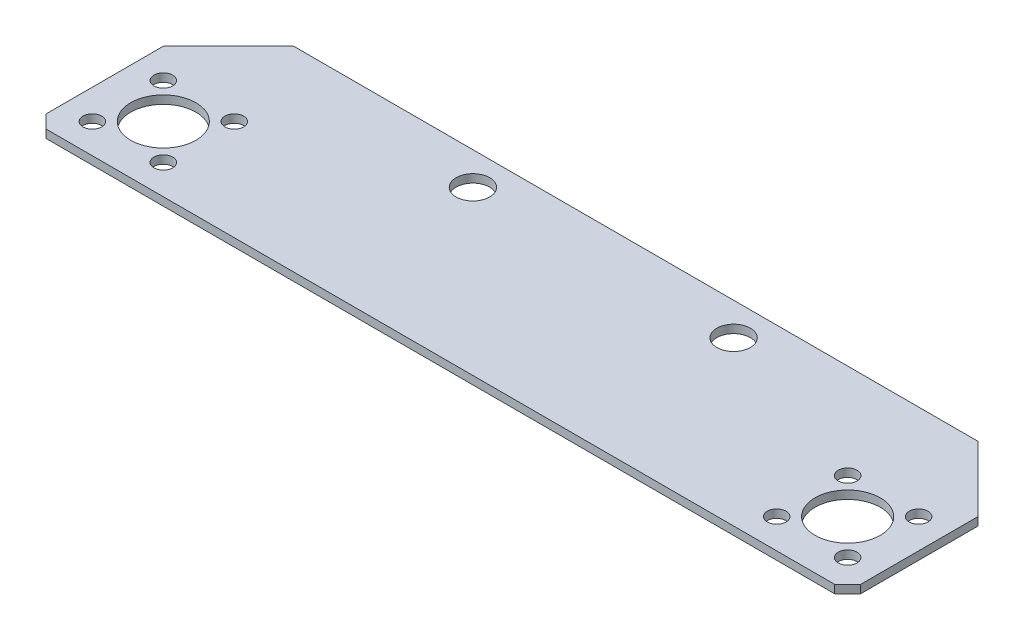
SolidWorks part; units mm, degrees
material "6061 Alloy"
ref_plane "Front Plane" through (0, 0, 0) normal (0, 0, 1) x (1, 0, 0)
ref_plane "Top Plane" through (0, 0, 0) normal (0, 1, 0) x (1, 0, 0)
ref_plane "Right Plane" through (0, 0, 0) normal (1, 0, 0) x (0, 0, -1)
sketch "Sketch1" plane through (0, 0, 0) normal (0, 1, 0) x (1, 0, 0)
  line L1 (0, 0) -> (158.75, 0)
  line L2 (0, 0) -> (0, 38.1)
  line L3 (0, 38.1) -> (158.75, 38.1)
  line L4 (158.75, 0) -> (158.75, 38.1)
  dimension "D1" = 38.1
  dimension "D2" = 158.75
extrude "Boss-Extrude1" add sketch "Sketch1" along normal blind 1.6002
hole_wizard "#27 (0.144) Diameter Hole1" positions "Sketch3" profile "Sketch2" hole size "#27" standard "ANSI Inch" end condition through all
sketch "Sketch3" plane through (0, 1.6002, 0) normal (0, 1, 0) x (1, 0, 0)
  line L0 (79.375, 0) -> (79.375, 38.1) construction
  line L1 (0, 0) -> (158.75, 0) construction
  line L2 (158.75, 38.1) -> (0, 38.1) construction
  line L3 (5.7852, 19.6148) -> (19.6148, 5.7852) construction
  line L6 (19.6148, 19.6148) -> (5.7852, 5.7852) construction
  line L11 (12.7, 12.7) -> (0, 12.7) construction
  line L14 (0, 38.1) -> (0, 0) construction
  point P9 (5.7852, 19.6148)
  point P11 (19.6148, 5.7852)
  point P13 (5.7852, 5.7852)
  point P15 (19.6148, 19.6148)
  point P43 (152.9648, 5.7852)
  point P44 (139.1352, 5.7852)
  point P45 (139.1352, 19.6148)
  point P46 (152.9648, 19.6148)
  dimension "D1" = 19.558
  dimension "D2" = 12.7
  dimension "D3" = 12.7
sketch "Sketch2" plane through (5.7852, 1.6002, -19.6148) normal (1, 0, 0) x (0, 0, 1)
  line L0 (0, 0) -> (0, 1.6002)
  line L1 (0, 1.6002) -> (1.8288, 1.6002)
  line L2 (1.8288, 1.6002) -> (1.8288, 0)
  line L5 (1.8288, 0) -> (0, 0)
  line L11 (0, -6.35) -> (0, 107.95) construction
  dimension "Thru Hole Dia." = 3.6576
  dimension "Thru Hole Depth" = 1.6002
hole_wizard "1/2 (0.5) Diameter Hole1" positions "Sketch5" profile "Sketch4" hole size "1/2" standard "ANSI Inch" end condition through all
sketch "Sketch5" plane through (0, 1.6002, 0) normal (0, 1, 0) x (1, 0, 0)
  line L0 (5.7852, 19.6148) -> (19.6148, 5.7852) construction
  line L3 (139.1352, 19.6148) -> (152.9648, 5.7852) construction
  point P0 (12.7, 12.7)
  point P2 (146.05, 12.7)
sketch "Sketch4" plane through (12.7, 1.6002, -12.7) normal (1, 0, 0) x (0, 0, 1)
  line L0 (0, 0) -> (0, 1.6002)
  line L1 (0, 1.6002) -> (6.35, 1.6002)
  line L2 (6.35, 1.6002) -> (6.35, 0)
  line L5 (6.35, 0) -> (0, 0)
  line L11 (0, -6.35) -> (0, 107.95) construction
  dimension "Thru Hole Dia." = 12.7
  dimension "Thru Hole Depth" = 1.6002
hole_wizard "F (0.257) Diameter Hole1" positions "Sketch7" profile "Sketch6" hole size "F" standard "ANSI Inch" end condition through all
sketch "Sketch7" plane through (0, 1.6002, 0) normal (0, 1, 0) x (1, 0, 0)
  line L0 (79.375, 38.1) -> (79.375, 31.75) construction
  line L1 (158.75, 38.1) -> (0, 38.1) construction
  line L4 (53.975, 31.75) -> (104.775, 31.75) construction
  point P0 (53.975, 31.75)
  point P2 (104.775, 31.75)
  dimension "D1" = 50.8
  dimension "D2" = 6.35
sketch "Sketch6" plane through (53.975, 1.6002, -31.75) normal (1, 0, 0) x (0, 0, 1)
  line L0 (0, 0) -> (0, 1.6002)
  line L1 (0, 1.6002) -> (3.2639, 1.6002)
  line L2 (3.2639, 1.6002) -> (3.2639, 0)
  line L5 (3.2639, 0) -> (0, 0)
  line L11 (0, -6.35) -> (0, 107.95) construction
  dimension "Thru Hole Dia." = 6.5278
  dimension "Thru Hole Depth" = 1.6002
chamfer "Chamfer1" distance 2.54 2 edges at (158.75, 0.8001, 0) (0, 0.8001, 0)
chamfer "Chamfer2" distance 12.7 angle 45 2 edges at (158.75, 0.8001, -38.1) (0, 0.8001, -38.1)
